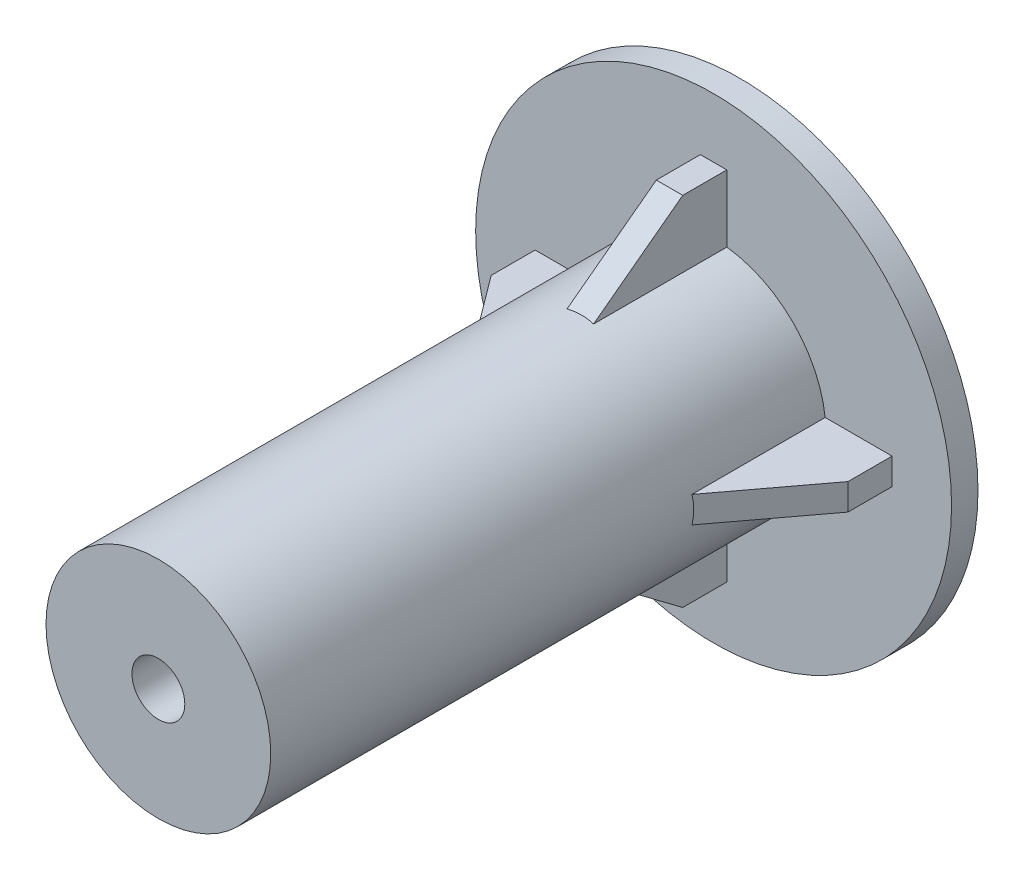
SolidWorks part; units mm, degrees
ref_plane "Front Plane" through (0, 0, 0) normal (0, 0, 1) x (1, 0, 0)
ref_plane "Top Plane" through (0, 0, 0) normal (0, 1, 0) x (1, 0, 0)
ref_plane "Right Plane" through (0, 0, 0) normal (1, 0, 0) x (0, 0, -1)
sketch "Sketch1" plane through (0, 0, 0) normal (0, 0, 1) x (1, 0, 0)
  circle A0 centre (0, 0) radius 42.5
  dimension "D1" = 85
extrude "Boss-Extrude1" add sketch "Sketch1" along normal blind 210
sketch "Sketch2" plane through (0, 0, 210) normal (0, 0, 1) x (1, 0, 0)
  circle A0 centre (0, 0) radius 10
  dimension "D1" = 20
extrude "Cut-Extrude1" cut sketch "Sketch2" against normal blind 20
sketch "Sketch3" plane through (0, 0, 0) normal (0, 0, -1) x (-1, 0, 0)
  circle A0 centre (0, 0) radius 90
  dimension "D1" = 180
extrude "Boss-Extrude2" add sketch "Sketch3" along normal blind 10
sketch "Sketch4" plane through (0, 0, 0) normal (0, 1, 0) x (1, 0, 0)
  line L0 (-42.5, -50) -> (-80, 0)
  line L1 (-42.5, 0) -> (-42.5, -210) construction
  line L2 (-90, 0) -> (90, 0) construction
  dimension "D1" = 50
  dimension "D2" = 80
rib "Rib1" sketch "Sketch4" sketch "Sketch4" thickness 10 extrusion direction parallel to sketch draft on no parameters "D1"=10
pattern_circular "CirPattern1" count 4 over 360 about axis through (0, 0, 0) along (0, 0, 1) of "Rib1"
sketch "Sketch5" plane through (0, 0, 0) normal (0, 0, 1) x (1, 0, 0)
  line L1 (67.5, 67.5) -> (-67.5, 67.5)
  line L2 (67.5, 67.5) -> (67.5, -67.5)
  line L3 (67.5, -67.5) -> (-67.5, -67.5)
  line L4 (-67.5, 67.5) -> (-67.5, -67.5)
  line L5 (67.5, 67.5) -> (-67.5, -67.5) construction
  line L6 (67.5, -67.5) -> (-67.5, 67.5) construction
  point P0 (0, 0)
  dimension "D1" = 135
extrude "Cut-Extrude2" cut sketch "Sketch5" along normal blind 94 flip side to cut
sketch "Sketch6" plane through (0, 0, -10) normal (0, 0, -1) x (-1, 0, 0)
  line L0 (0, 0) -> (-200, 0) construction
  line L1 (0, 0) -> (0, 200) construction
  text T0 "Y0\r\n" font "Century Gothic" height 20
  text T1 "X0\r\n" font "Century Gothic" height 20
  dimension "D1" = 200
sketch "Sketch7" plane through (0, 0, 0) normal (0, 1, 0) x (1, 0, 0)
  line L0 (0, 10) -> (0, -140) construction
  line L1 (0, 10) -> (200, 10) construction
  text T0 "Z0\r\n" font "Century Gothic" height 20
  point P4 (0.6257, 1.5176)
  point P7 (0.8628, 2.8849)
  point P8 (0, 0)
  point P9 (0, 0)
  point P10 (0.4603, 5.25)
  point P11 (0.3093, 10)
  dimension "D1" = 150
